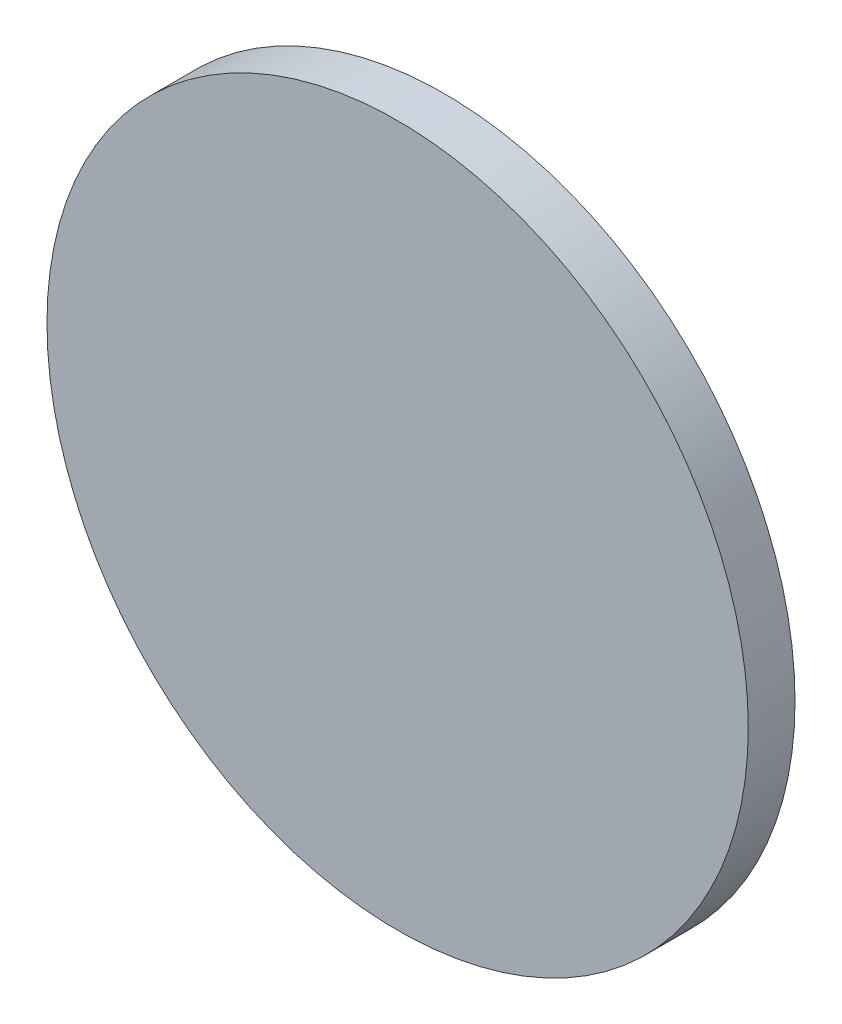
SolidWorks part; units mm, degrees
ref_plane "前视基准面" through (0, 0, 0) normal (0, 0, 1) x (1, 0, 0)
ref_plane "上视基准面" through (0, 0, 0) normal (0, 1, 0) x (1, 0, 0)
ref_plane "右视基准面" through (0, 0, 0) normal (1, 0, 0) x (0, 0, -1)
sketch "草图1" plane through (0, 0, 0) normal (0, 0, 1) x (1, 0, 0)
  circle A0 centre (0, 0) radius 60
  dimension "D1" = 120
extrude "凸台-拉伸1" add sketch "草图1" along normal blind 8
